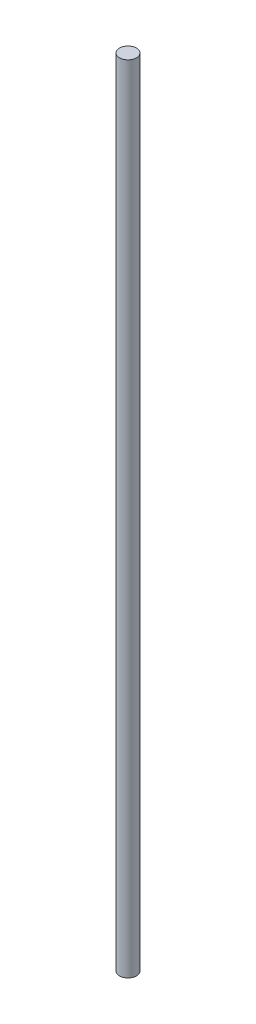
SolidWorks part; units mm, degrees
ref_plane "Front Plane" through (0, 0, 0) normal (0, 0, 1) x (1, 0, 0)
ref_plane "Top Plane" through (0, 0, 0) normal (0, 1, 0) x (1, 0, 0)
ref_plane "Right Plane" through (0, 0, 0) normal (1, 0, 0) x (0, 0, -1)
sketch "Sketch1" plane through (0, 0, 0) normal (0, 1, 0) x (1, 0, 0)
  circle A0 centre (0, 0) radius 4
  dimension "D1" = 8
extrude "Boss-Extrude1" add sketch "Sketch1" along normal blind 375
